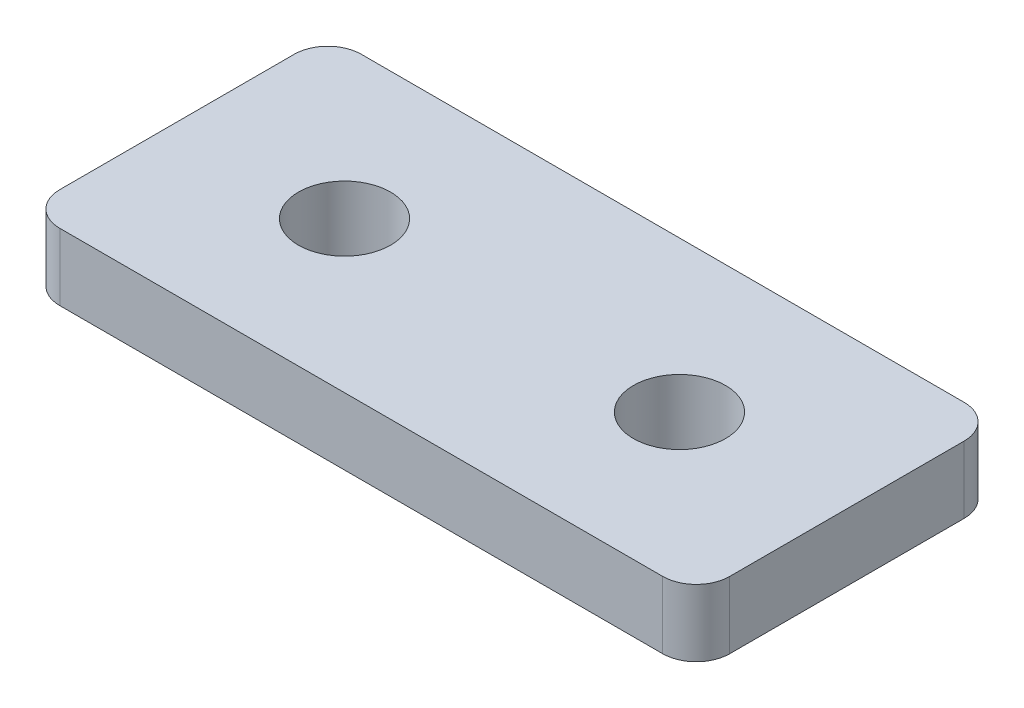
SolidWorks part; units mm, degrees
ref_plane "前视基准面" through (0, 0, 0) normal (0, 0, 1) x (1, 0, 0)
ref_plane "上视基准面" through (0, 0, 0) normal (0, 1, 0) x (1, 0, 0)
ref_plane "右视基准面" through (0, 0, 0) normal (1, 0, 0) x (0, 0, -1)
sketch "草图1" plane through (0, 0, 0) normal (0, 1, 0) x (1, 0, 0)
  line L0 (0, 0) -> (23.929, 0) construction
  line L1 (0, 0) -> (0, 14.5261) construction
  line L3 (-20, -9) -> (20, -9)
  line L4 (-20, -9) -> (-20, 9)
  line L5 (-20, 9) -> (20, 9)
  line L6 (20, -9) -> (20, 9)
  line L7 (-20, -9) -> (20, 9) construction
  line L8 (-20, 9) -> (20, -9) construction
  point P1 (0, 0)
  dimension "D1" = 18
  dimension "D2" = 40
extrude "凸台-拉伸1" add sketch "草图1" along normal blind 4
sketch "草图2" plane through (0, 4, 0) normal (0, 1, 0) x (1, 0, 0)
  line L0 (0, 0) -> (0, 13.6865) construction
  line L1 (-20, 9) -> (-20, -9) construction
  circle A0 centre (-10, 0) radius 2.75
  circle A1 centre (10, 0) radius 2.75
  dimension "D1" = 5.5
  dimension "D2" = 10
extrude "切除-拉伸1" cut sketch "草图2" against normal blind 4
fillet "圆角1" radius 2 4 edges at (-20, 2, 9) (-20, 2, -9) (20, 2, -9) (20, 2, 9)
